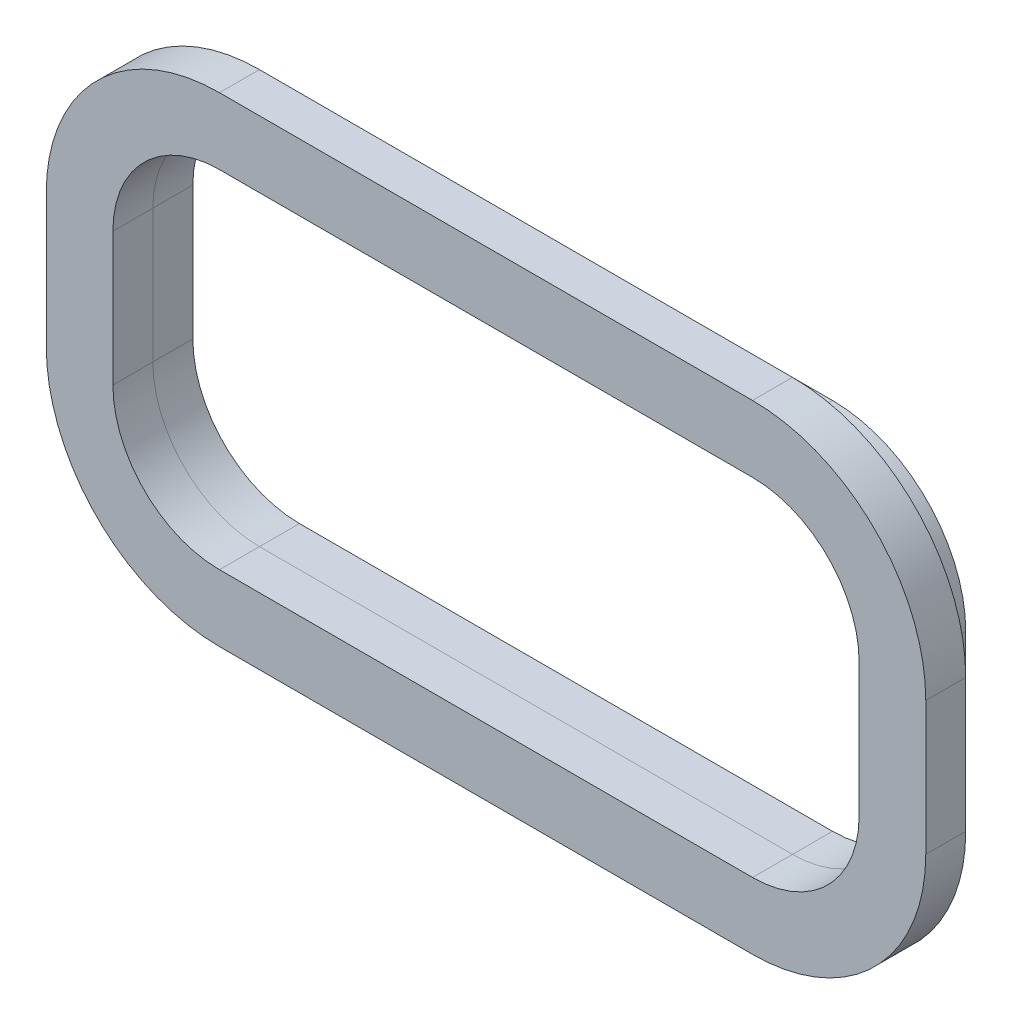
SolidWorks part; units mm, degrees
ref_plane "Plan de face" through (0, 0, 0) normal (0, 0, 1) x (1, 0, 0)
ref_plane "Plan de dessus" through (0, 0, 0) normal (0, 1, 0) x (1, 0, 0)
ref_plane "Plan de droite" through (0, 0, 0) normal (1, 0, 0) x (0, 0, -1)
sketch "Esquisse2" plane through (0, 0, 0) normal (0, 0, 1) x (1, 0, 0)
  line L0 (28.6783, -4.6265) -> (28.6783, 5.3735)
  line L1 (-21.3217, -14.6265) -> (18.6783, -14.6265)
  line L2 (-31.3217, 5.3735) -> (-31.3217, -4.6265)
  line L3 (18.6783, 15.3735) -> (-21.3217, 15.3735)
  line L4 (26.6783, -4.6265) -> (26.6783, 5.3735)
  line L5 (18.6783, 13.3735) -> (-21.3217, 13.3735)
  line L6 (-29.3217, 5.3735) -> (-29.3217, -4.6265)
  line L7 (-21.3217, -12.6265) -> (18.6783, -12.6265)
  arc A0 (28.6783, 5.3735) -> (18.6783, 15.3735) centre (18.6783, 5.3735) ccw
  arc A1 (18.6783, -14.6265) -> (28.6783, -4.6265) centre (18.6783, -4.6265) ccw
  arc A2 (-31.3217, -4.6265) -> (-21.3217, -14.6265) centre (-21.3217, -4.6265) ccw
  arc A3 (-21.3217, 15.3735) -> (-31.3217, 5.3735) centre (-21.3217, 5.3735) ccw
  arc A4 (26.6783, 5.3735) -> (18.6783, 13.3735) centre (18.6783, 5.3735) ccw
  arc A5 (-21.3217, 13.3735) -> (-29.3217, 5.3735) centre (-21.3217, 5.3735) ccw
  arc A6 (-29.3217, -4.6265) -> (-21.3217, -12.6265) centre (-21.3217, -4.6265) ccw
  arc A7 (18.6783, -12.6265) -> (26.6783, -4.6265) centre (18.6783, -4.6265) ccw
  dimension "D1" = 2
extrude "Boss.-Extru.1" add sketch "Esquisse2" along normal blind 3
sketch "Esquisse3" plane through (0, 0, 3) normal (0, 0, 1) x (1, 0, 0)
  line L0 (18.6783, 18.3735) -> (-21.3217, 18.3735)
  line L1 (-34.3217, 5.3735) -> (-34.3217, -4.6265)
  line L2 (-21.3217, -17.6265) -> (18.6783, -17.6265)
  line L3 (31.6783, -4.6265) -> (31.6783, 5.3735)
  line L4 (18.6783, 15.3735) -> (-21.3217, 15.3735)
  line L5 (-31.3217, 5.3735) -> (-31.3217, -4.6265)
  line L6 (-21.3217, -14.6265) -> (18.6783, -14.6265)
  line L7 (28.6783, -4.6265) -> (28.6783, 5.3735)
  line L8 (18.6783, 15.3735) -> (-21.3217, 15.3735)
  line L20 (-31.3217, 5.3735) -> (-31.3217, -4.6265) construction
  line L21 (-21.3217, -14.6265) -> (18.6783, -14.6265) construction
  line L22 (28.6783, -4.6265) -> (28.6783, 5.3735) construction
  arc A0 (31.6783, 5.3735) -> (18.6783, 18.3735) centre (18.6783, 5.3735) ccw
  arc A1 (-21.3217, 18.3735) -> (-34.3217, 5.3735) centre (-21.3217, 5.3735) ccw
  arc A2 (-34.3217, -4.6265) -> (-21.3217, -17.6265) centre (-21.3217, -4.6265) ccw
  arc A3 (18.6783, -17.6265) -> (31.6783, -4.6265) centre (18.6783, -4.6265) ccw
  arc A4 (28.6783, 5.3735) -> (18.6783, 15.3735) centre (18.6783, 5.3735) ccw
  arc A5 (-21.3217, 15.3735) -> (-31.3217, 5.3735) centre (-21.3217, 5.3735) ccw
  arc A6 (-31.3217, -4.6265) -> (-21.3217, -14.6265) centre (-21.3217, -4.6265) ccw
  arc A7 (18.6783, -14.6265) -> (28.6783, -4.6265) centre (18.6783, -4.6265) ccw
  arc A20 (-21.3217, 15.3735) -> (-31.3217, 5.3735) centre (-21.3217, 5.3735) ccw construction
  arc A21 (-31.3217, -4.6265) -> (-21.3217, -14.6265) centre (-21.3217, -4.6265) ccw construction
  arc A22 (18.6783, -14.6265) -> (28.6783, -4.6265) centre (18.6783, -4.6265) ccw construction
  arc A23 (28.6783, 5.3735) -> (18.6783, 15.3735) centre (18.6783, 5.3735) ccw construction
  arc M17 (28.6783, 5.3735) -> (18.6783, 15.3735) centre (18.6783, 5.3735) ccw
  line M18 (18.6783, 15.3735) -> (-21.3217, 15.3735)
  arc M19 (-21.3217, 15.3735) -> (-31.3217, 5.3735) centre (-21.3217, 5.3735) ccw
  line M20 (-31.3217, 5.3735) -> (-31.3217, -4.6265)
  arc M21 (-31.3217, -4.6265) -> (-21.3217, -14.6265) centre (-21.3217, -4.6265) ccw
  line M22 (-21.3217, -14.6265) -> (18.6783, -14.6265)
  arc M23 (18.6783, -14.6265) -> (28.6783, -4.6265) centre (18.6783, -4.6265) ccw
  line M24 (28.6783, -4.6265) -> (28.6783, 5.3735)
  line M25 (26.6783, 5.3735) -> (26.6783, -4.6265)
  arc M26 (26.6783, -4.6265) -> (18.6783, -12.6265) centre (18.6783, -4.6265) cw
  line M27 (18.6783, -12.6265) -> (-21.3217, -12.6265)
  arc M28 (-21.3217, -12.6265) -> (-29.3217, -4.6265) centre (-21.3217, -4.6265) cw
  line M29 (-29.3217, -4.6265) -> (-29.3217, 5.3735)
  arc M30 (-29.3217, 5.3735) -> (-21.3217, 13.3735) centre (-21.3217, 5.3735) cw
  line M31 (-21.3217, 13.3735) -> (18.6783, 13.3735)
  arc M32 (18.6783, 13.3735) -> (26.6783, 5.3735) centre (18.6783, 5.3735) cw
  dimension "D1" = 0
  dimension "D2" = 3
extrude "Boss.-Extru.2" add sketch "Esquisse3" along normal blind 3 separate body contours L2 A3 L3 A0 L0 A1 L1 A2 M17 M24 M23 M22 M21 M20 M19 M18 | M25 M32 M31 M30 M29 M28 M27 M26 | M24 M17 M18 M19 M20 M21 M22 M23 M32 M25 M26 M27 M28 M29 M30 M31
sketch "Esquisse4" plane through (0, 0, 3) normal (0, 0, -1) x (-1, 0, 0)
  line L4 (-28.6783, 5.3735) -> (-28.6783, -4.6265)
  line L5 (21.3217, 15.3735) -> (-18.6783, 15.3735)
  line L6 (31.3217, -4.6265) -> (31.3217, 5.3735)
  line L7 (-18.6783, -14.6265) -> (21.3217, -14.6265)
  line L8 (-28.6783, 5.3735) -> (-28.6783, -4.6265)
  line L9 (21.3217, 15.3735) -> (-18.6783, 15.3735)
  line L10 (31.3217, -4.6265) -> (31.3217, 5.3735)
  line L11 (-18.6783, -14.6265) -> (21.3217, -14.6265)
  line L12 (21.3217, 13.3735) -> (-18.6783, 13.3735)
  line L13 (-26.6783, 5.3735) -> (-26.6783, -4.6265)
  line L14 (-18.6783, -12.6265) -> (21.3217, -12.6265)
  line L15 (29.3217, -4.6265) -> (29.3217, 5.3735)
  line L16 (21.3217, 13.3735) -> (-18.6783, 13.3735)
  line L17 (-26.6783, 5.3735) -> (-26.6783, -4.6265)
  line L18 (-18.6783, -12.6265) -> (21.3217, -12.6265)
  line L19 (29.3217, -4.6265) -> (29.3217, 5.3735)
  arc A4 (-18.6783, 15.3735) -> (-28.6783, 5.3735) centre (-18.6783, 5.3735) ccw
  arc A5 (31.3217, 5.3735) -> (21.3217, 15.3735) centre (21.3217, 5.3735) ccw
  arc A6 (21.3217, -14.6265) -> (31.3217, -4.6265) centre (21.3217, -4.6265) ccw
  arc A7 (-28.6783, -4.6265) -> (-18.6783, -14.6265) centre (-18.6783, -4.6265) ccw
  arc A8 (-18.6783, 15.3735) -> (-28.6783, 5.3735) centre (-18.6783, 5.3735) ccw
  arc A9 (31.3217, 5.3735) -> (21.3217, 15.3735) centre (21.3217, 5.3735) ccw
  arc A10 (21.3217, -14.6265) -> (31.3217, -4.6265) centre (21.3217, -4.6265) ccw
  arc A11 (-28.6783, -4.6265) -> (-18.6783, -14.6265) centre (-18.6783, -4.6265) ccw
  arc A12 (-18.6783, 13.3735) -> (-26.6783, 5.3735) centre (-18.6783, 5.3735) ccw
  arc A13 (-26.6783, -4.6265) -> (-18.6783, -12.6265) centre (-18.6783, -4.6265) ccw
  arc A14 (21.3217, -12.6265) -> (29.3217, -4.6265) centre (21.3217, -4.6265) ccw
  arc A15 (29.3217, 5.3735) -> (21.3217, 13.3735) centre (21.3217, 5.3735) ccw
  arc A16 (-18.6783, 13.3735) -> (-26.6783, 5.3735) centre (-18.6783, 5.3735) ccw
  arc A17 (-26.6783, -4.6265) -> (-18.6783, -12.6265) centre (-18.6783, -4.6265) ccw
  arc A18 (21.3217, -12.6265) -> (29.3217, -4.6265) centre (21.3217, -4.6265) ccw
  arc A19 (29.3217, 5.3735) -> (21.3217, 13.3735) centre (21.3217, 5.3735) ccw
  dimension "D1" = 0
  dimension "D2" = 0
extrude "Enlèv. mat.-Extru.1" cut sketch "Esquisse4" against normal through all contours L16 A16 L17 A17 L18 A18 L19 A19
